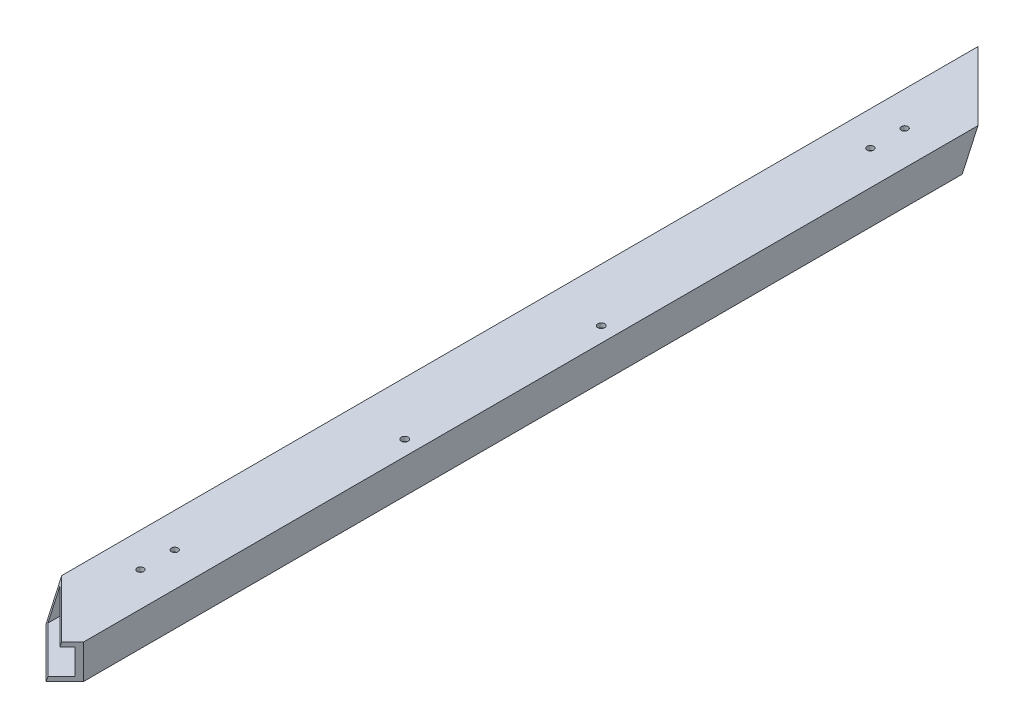
SolidWorks part; units mm, degrees
material "1060 Alloy"
ref_plane "Front Plane" through (0, 0, 0) normal (0, 0, 1) x (1, 0, 0)
ref_plane "Top Plane" through (0, 0, 0) normal (0, 1, 0) x (1, 0, 0)
ref_plane "Right Plane" through (0, 0, 0) normal (1, 0, 0) x (0, 0, -1)
sketch "Sketch1" plane through (0, 0, 0) normal (0, 0, 1) x (1, 0, 0)
  line L0 (-22.225, 9.525) -> (22.225, 9.525)
  line L1 (-25.4, -12.7) -> (25.4, -12.7)
  line L2 (-25.4, -12.7) -> (-25.4, 12.7)
  line L3 (-25.4, 12.7) -> (25.4, 12.7)
  line L4 (25.4, -12.7) -> (25.4, 12.7)
  line L5 (-25.4, -12.7) -> (25.4, 12.7) construction
  line L6 (-25.4, 12.7) -> (25.4, -12.7) construction
  line L7 (22.225, -9.525) -> (22.225, 9.525)
  line L8 (-22.225, -9.525) -> (22.225, -9.525)
  line L9 (-22.225, -9.525) -> (-22.225, 9.525)
  point P0 (0, 0)
  dimension "D1" = 25.4
  dimension "D2" = 50.8
  dimension "D3" = 3.175
extrude "Boss-Extrude1" add sketch "Sketch1" along normal blind 771.9314
sketch "Sketch2" plane through (0, 12.7, 0) normal (0, 1, 0) x (1, 0, 0)
  line L0 (-25.4, 0) -> (25.4, -50.8)
  line L1 (25.4, -771.9314) -> (25.4, 0) construction
  line L2 (25.4, -50.8) -> (25.4, 0)
  line L3 (25.4, 0) -> (-25.4, 0)
  line L4 (25.4, -771.9314) -> (-25.4, -721.1314)
  line L5 (-25.4, -771.9314) -> (-25.4, 0) construction
  line L6 (-25.4, -721.1314) -> (-25.4, -771.9314)
  line L7 (-25.4, -771.9314) -> (25.4, -771.9314)
  dimension "D1" = 45
  dimension "D2" = 45
extrude "Cut-Extrude1" cut sketch "Sketch2" against normal blind 771.9314
sketch "Sketch3" plane through (0, 12.7, 0) normal (0, 1, 0) x (1, 0, 0)
  line L0 (-3.3782, -743.1532) -> (25.4, -714.375)
  line L1 (25.4, -771.9314) -> (-25.4, -721.1314) construction
  line L2 (25.4, -771.9314) -> (25.4, -50.8) construction
  line L3 (25.4, -714.375) -> (25.4, -771.9314)
  line L4 (25.4, -771.9314) -> (-3.3782, -771.9314)
  line L5 (-3.3782, -771.9314) -> (-3.3782, -743.1532)
  point P9 (-3.3782, -757.5423)
  dimension "D1" = 28.7782
  dimension "D2" = 45
extrude "Cut-Extrude2" cut sketch "Sketch3" against normal through all
ref_plane "Plane1" through (-12.7, 0, -12.7) normal (0.7071, 0, 0.7071) x (0, -1, 0)
sketch "Sketch4" plane through (-12.7, 0, -12.7) normal (0.7071, 0, 0.7071) x (0, -1, 0)
  line L0 (-12.7, -17.9605) -> (12.7, -26.2135)
  line L1 (12.7, -527.8774) -> (12.7, -17.9605) construction
  line L2 (12.7, -26.2135) -> (12.7, -17.9605)
  line L3 (12.7, -17.9605) -> (-12.7, -17.9605)
  dimension "D1" = 18
extrude "Cut-Extrude3" cut sketch "Sketch4" along normal through all
sketch "Sketch6" plane through (369.8875, 0, 369.8875) normal (0.7071, 0, 0.7071) x (0.7071, 0, -0.7071)
  line L0 (-506.9655, 12.7) -> (-506.9655, -12.7) construction
  line L1 (-487.1789, 12.7) -> (-527.8774, 12.7) construction
  line L2 (-487.1789, -12.7) -> (-527.8774, -12.7) construction
  line L3 (-506.9655, -12.7) -> (-498.7125, 12.7)
  line L4 (-498.7125, 12.7) -> (-506.9655, 12.7)
  line L5 (-487.1789, -12.7) -> (-487.1789, 12.7) construction
  line L6 (-506.9655, 12.7) -> (-527.8774, 12.7)
  line L7 (-506.9655, 12.7) -> (-506.9655, -12.7) construction
  line L8 (-506.9655, -12.7) -> (-527.8774, -12.7)
  line L9 (-527.8774, 12.7) -> (-527.8774, -12.7)
  dimension "D1" = 18
  dimension "D2" = 19.7866
extrude "Cut-Extrude5" cut sketch "Sketch6" against normal blind 771.9314
sketch "Sketch7" plane through (0, -12.7, 0) normal (0, -1, 0) x (1, 0, 0)
  circle A0 centre (0, 105.2577) radius 2.4638
  circle A1 centre (0, 79.8577) radius 2.4638
  dimension "D1" = 4.9276
extrude "Cut-Extrude6" cut sketch "Sketch7" against normal through all
sketch "Sketch8" plane through (0, 12.7, 0) normal (0, 1, 0) x (1, 0, 0)
  circle A0 centre (0, -646.8677) radius 2.4638
  circle A1 centre (0, -621.4677) radius 2.4638
  dimension "D1" = 4.9276
  dimension "D2" = 4.9276
extrude "Cut-Extrude7" cut sketch "Sketch8" against normal through all
hole_wizard "13/64 (0.20313) Diameter Hole1" positions "Sketch9" profile "Sketch10" hole size "13/64" standard "ANSI Inch" end condition through all
sketch "Sketch9" plane through (0, -12.7, 0) normal (0, -1, 0) x (-1, 0, 0)
  point P0 (-14.2367, -319.1722)
  point P3 (-14.2367, -464.9682)
sketch "Sketch10" plane through (14.2367, -12.7, 319.1722) normal (1, 0, 0) x (0, 0, -1)
  line L0 (0, 0) -> (0, 25.4)
  line L1 (0, 25.4) -> (2.5798, 25.4)
  line L2 (2.5798, 25.4) -> (2.5798, 0)
  line L5 (2.5798, 0) -> (0, 0)
  line L11 (0, -6.35) -> (0, 107.95) construction
  dimension "Thru Hole Dia." = 5.1595
  dimension "Thru Hole Depth" = 25.4
